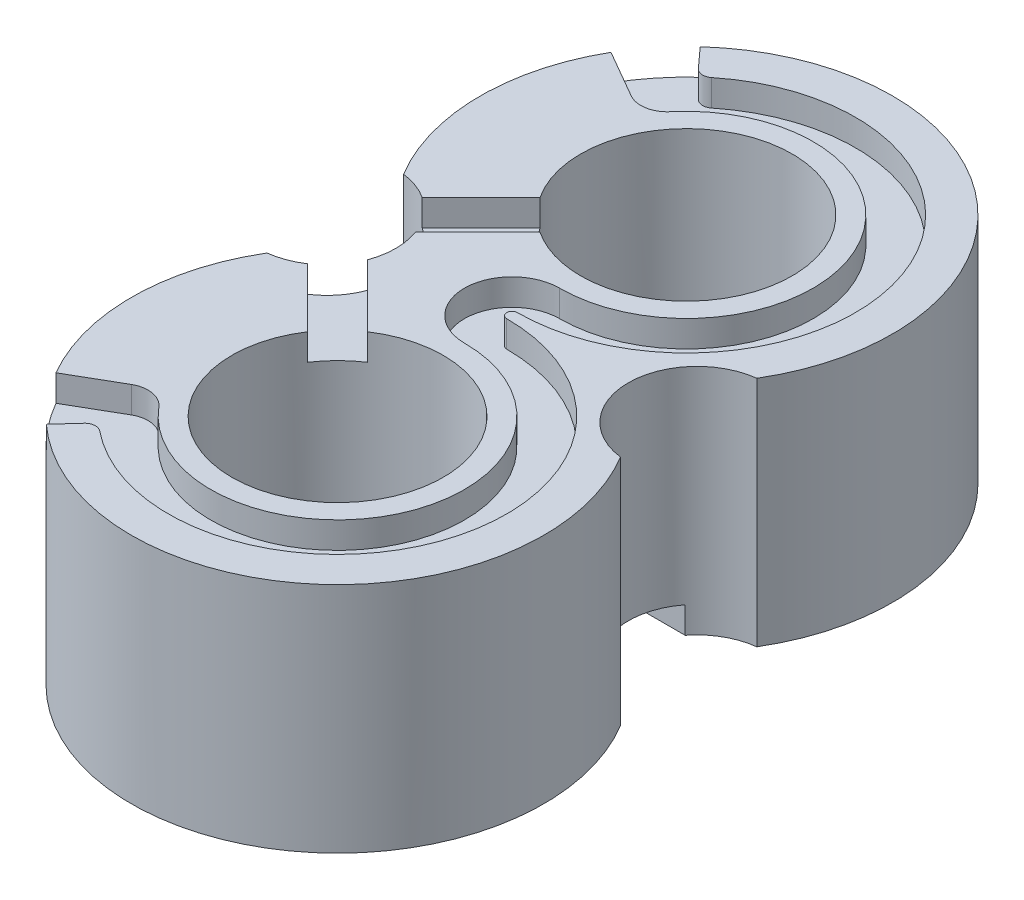
SolidWorks part; units mm, degrees
ref_plane "前视基准面" through (0, 0, 0) normal (0, 0, 1) x (1, 0, 0)
ref_plane "上视基准面" through (0, 0, 0) normal (0, 1, 0) x (1, 0, 0)
ref_plane "右视基准面" through (0, 0, 0) normal (1, 0, 0) x (0, 0, -1)
sketch "草图1" plane through (0, 0, 0) normal (0, 1, 0) x (1, 0, 0)
  line L0 (0, -33) -> (0, 0) construction
  circle A0 centre (0, 0) radius 19.5
  circle A1 centre (0, -33) radius 19.5
  dimension "D1" = 39
  dimension "D2" = 33
extrude "凸台-拉伸1" add sketch "草图1" along normal blind 22
sketch "草图2" plane through (0, 22, 0) normal (0, 1, 0) x (1, 0, 0)
  circle A0 centre (0, 0) radius 10
  circle A1 centre (0, -33) radius 10
  arc A2 (-10.3923, -16.5) -> (10.3923, -16.5) centre (0, -33) ccw construction
  dimension "D1" = 20
extrude "切除-拉伸1" cut sketch "草图2" against normal through all both and the other way through all
sketch "草图3" plane through (0, 22, 0) normal (0, 1, 0) x (1, 0, 0)
  line L0 (0, -33) -> (0, 0) construction
  line L1 (0, 0) -> (-16.8875, 9.75) construction
  line L2 (0, 0) -> (-13.1238, 14.4228) construction
  line L3 (-12.3693, 7.1414) -> (-16.8875, 9.75)
  line L4 (-11.4215, 12.5519) -> (-13.1238, 14.4228)
  line L5 (0, -16.5) -> (20.5289, -16.5) construction
  line L6 (0, -33) -> (-13.1238, -47.4228) construction
  line L7 (0, -33) -> (-16.8875, -42.75) construction
  line L8 (-11.4215, -45.5519) -> (-13.1238, -47.4228)
  line L9 (-12.3693, -40.1414) -> (-16.8875, -42.75)
  arc A0 (0, -16) -> (-10.0535, 12.447) centre (0, 0) ccw
  circle A1 centre (0, -33) radius 16 construction
  circle A2 centre (0, -33) radius 10 construction
  arc A3 (0, -12) -> (-9.2022, 7.7019) centre (0, 0) ccw
  circle A4 centre (0, -33) radius 12 construction
  arc A5 (0, -12) -> (0, -21) centre (0, -16.5) ccw
  arc A6 (0, -16) -> (0, -17) centre (0, -16.5) ccw
  arc A7 (-9.2022, 7.7019) -> (-12.3693, 7.1414) centre (-11.1193, 9.3065) cw
  arc A8 (-10.0535, 12.447) -> (-11.4215, 12.5519) centre (-10.6818, 13.2249) cw
  arc A9 (-10.3923, -16.5) -> (10.3923, -16.5) centre (0, -33) ccw
  arc A10 (10.3923, -16.5) -> (-10.3923, -16.5) centre (0, 0) ccw
  arc A11 (-10.3923, -16.5) -> (10.3923, -16.5) centre (0, -33) ccw
  arc A12 (10.3923, -16.5) -> (-10.3923, -16.5) centre (0, 0) ccw
  arc A13 (10.3923, -16.5) -> (-10.3923, -16.5) centre (0, -33) cw
  arc A14 (-10.0535, -45.447) -> (-11.4215, -45.5519) centre (-10.6818, -46.2249) ccw
  arc A15 (-9.2022, -40.7019) -> (-12.3693, -40.1414) centre (-11.1193, -42.3065) ccw
  arc A16 (0, -21) -> (-9.2022, -40.7019) centre (0, -33) cw
  arc A17 (0, -17) -> (-10.0535, -45.447) centre (0, -33) cw
  point P22 (-10.3923, 6)
  point P25 (-10.7682, 11.8341)
  point P36 (-10.7682, -44.8341)
  point P37 (-10.3923, -39)
  arc M14 (-10.3923, -16.5) -> (10.3923, -16.5) centre (0, -33) ccw
  arc M15 (10.3923, -16.5) -> (-10.3923, -16.5) centre (0, 0) ccw
  dimension "D1" = 32
  dimension "D2" = 24
  dimension "D3" = 9
  dimension "D4" = 1
  dimension "D8" = 2.5
  dimension "D9" = 1
  dimension "D6" = 60
  dimension "D7" = 6
  dimension "D5" = 0
extrude "切除-拉伸2" cut sketch "草图3" against normal blind 2.5 contours A17 A6 A0 A8 L4 L3 A7 A3 A5 A16 A15 L9 L8 A14 M15 M14
sketch "草图4" plane through (0, 22, 0) normal (0, 1, 0) x (1, 0, 0)
  line L0 (0, -33) -> (0, 0) construction
  line L1 (17.5, -16.5) -> (-17.5, -16.5) construction
  circle A0 centre (17.5, -16.5) radius 6.5
  circle A2 centre (-17.5, -16.5) radius 6.5
  point P6 (11, -16.5)
  point P9 (0, -16.5)
  point P10 (-11, -16.5)
  dimension "D1" = 13
  dimension "D2" = 22
extrude "凸台-拉伸2" add sketch "草图4" against normal up to surface (22 mm away)
sketch "草图5" plane through (0, 22, 0) normal (0, 1, 0) x (1, 0, 0)
  circle A0 centre (17.5, -16.5) radius 6.5 construction
  circle A1 centre (-17.5, -16.5) radius 6.5 construction
  circle A2 centre (17.5, -16.5) radius 6.5
  circle A3 centre (-17.5, -16.5) radius 6.5
extrude "切除-拉伸4" cut sketch "草图5" against normal through all both and the other way through all
sketch "草图6" plane through (0, 0, 0) normal (0, -1, 0) x (1, 0, 0)
  line L0 (0, 33) -> (0, 0) construction
  line L1 (35, 12.5) -> (-35, 12.5)
  line L2 (35, 12.5) -> (35, 20.5)
  line L3 (35, 20.5) -> (-35, 20.5)
  line L4 (-35, 12.5) -> (-35, 20.5)
  line L5 (35, 12.5) -> (-35, 20.5) construction
  line L6 (35, 20.5) -> (-35, 12.5) construction
  line L8 (-2, 20.5) -> (2, 20.5)
  line L9 (-2, 20.5) -> (-2, 12.5)
  line L10 (-2, 12.5) -> (2, 12.5)
  line L11 (2, 20.5) -> (2, 12.5)
  line L12 (-2, 20.5) -> (2, 12.5) construction
  line L13 (-2, 12.5) -> (2, 20.5) construction
  point P0 (0, 16.5)
  point P10 (0, 16.5)
  arc M7 (16.7119, 10.0479) -> (16.7119, 22.9521) centre (17.5, 16.5) cw
  arc M9 (-16.7119, 22.9521) -> (-16.7119, 10.0479) centre (-17.5, 16.5) cw
  dimension "D1" = 8
  dimension "D2" = 70
  dimension "D3" = 4
extrude "切除-拉伸5" cut sketch "草图6" against normal blind 2.5 contours L9 L3 L1 M9 | L3 L11 L1 M7
fillet "圆角1" radius 1 4 edges at (-2, 1.25, 20.5) (-2, 1.25, 12.5) (2, 1.25, 12.5) (2, 1.25, 20.5)
sketch "草图7" plane through (0, 22, 0) normal (0, 1, 0) x (1, 0, 0)
  line L0 (0, 0) -> (-16.5, -16.5) construction
  line L1 (0, 0) -> (0, -33) construction
  line L2 (-1.4142, 1.4142) -> (-17.9142, -15.0858)
  line L3 (1.4142, -1.4142) -> (-15.0858, -17.9142)
  line L4 (0, -33) -> (-16.5, -16.5) construction
  line L5 (1.4142, -31.5858) -> (-13.6716, -16.5)
  line L6 (-1.4142, -34.4142) -> (-15.5038, -20.3246)
  line L7 (1.4142, -31.5858) -> (-12.6754, -17.4962) construction
  line L8 (0, -33) -> (-14.0896, -18.9104) construction
  line L9 (-1.4142, -34.4142) -> (1.4142, -31.5858)
  line L10 (1.4142, -1.4142) -> (-1.4142, 1.4142)
  line L11 (-15.5038, -20.3246) -> (-19.3284, -16.5)
  line L12 (-19.3284, -16.5) -> (-17.9142, -15.0858)
  dimension "D1" = 45
  dimension "D4" = 45
  dimension "D2" = 2
  dimension "D3" = 2
  dimension "D5" = 2
  dimension "D6" = 2
extrude "切除-拉伸6" cut sketch "草图7" against normal blind 2.5
equation "\"、\"=22"
